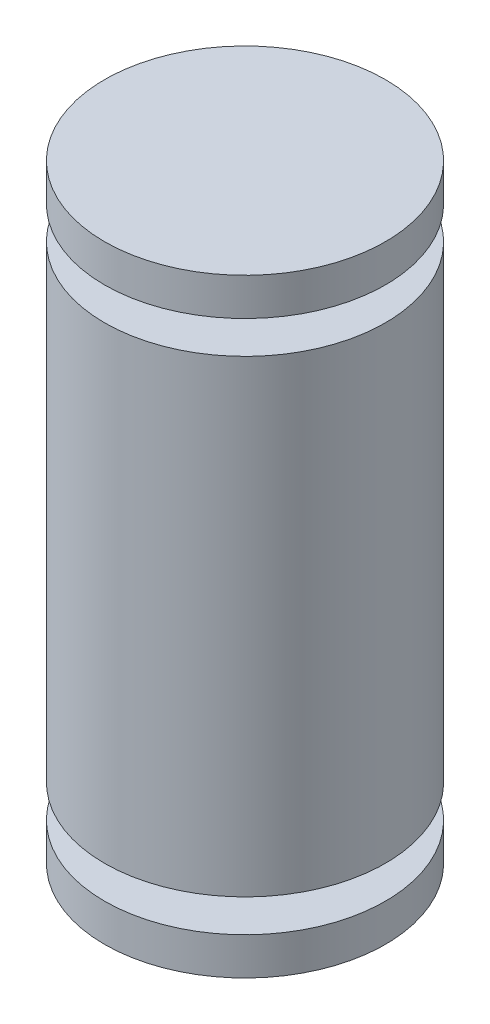
SolidWorks part; units mm, degrees
ref_plane "Front Plane" through (0, 0, 0) normal (0, 0, 1) x (1, 0, 0)
ref_plane "Top Plane" through (0, 0, 0) normal (0, 1, 0) x (1, 0, 0)
ref_plane "Right Plane" through (0, 0, 0) normal (1, 0, 0) x (0, 0, -1)
sketch "Sketch1" plane through (0, 0, 0) normal (0, 0, 1) x (1, 0, 0)
  line L16 (0, 2.5) -> (0, 12.5)
  line L17 (0, 12.5) -> (-1, 12.5)
  line L18 (-1, 12.5) -> (-1, 13.2)
  line L19 (-1, 13.2) -> (0, 13.2)
  line L20 (0, 13.2) -> (0, 14)
  line L21 (0, 14) -> (-3, 14)
  line L24 (0, 7.5) -> (-1.3205, 7.5) construction
  line L26 (0, 2.5) -> (-1, 2.5)
  line L27 (-1, 2.5) -> (-1, 1.8)
  line L28 (-1, 1.8) -> (0, 1.8)
  line L29 (0, 1.8) -> (0, 1)
  line L30 (-3, 14) -> (-3, 1)
  line L31 (-3, 1) -> (0, 1)
  dimension "D2" = 0.7
  dimension "D4" = 1
  dimension "D5" = 3
  dimension "D6" = 0.8
revolve "Revolve1" add sketch "Sketch1" angle 360 about L30
